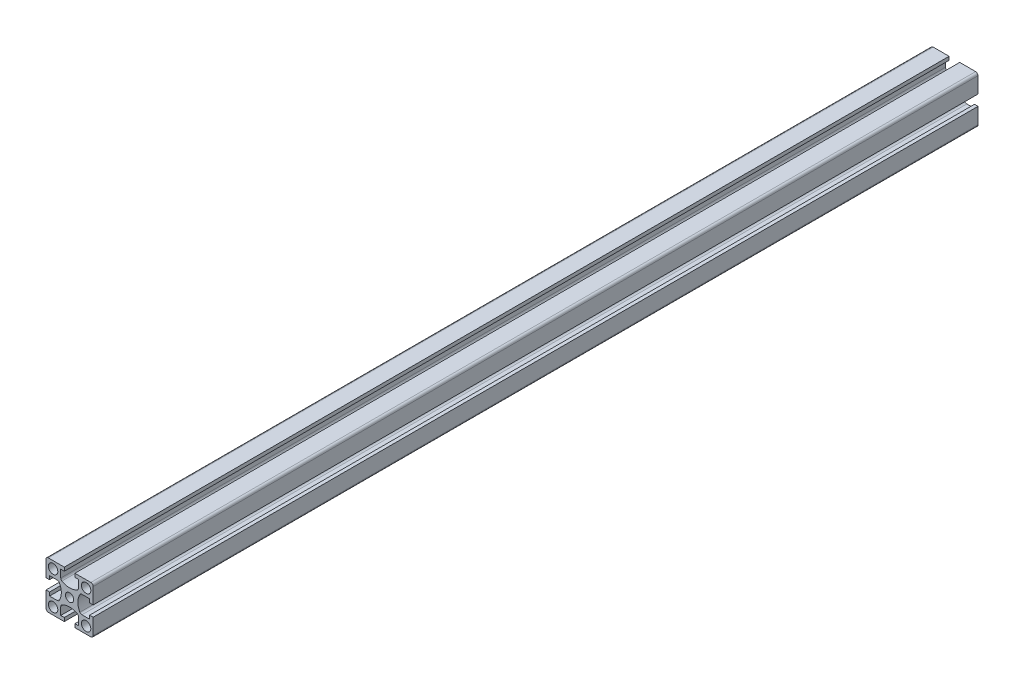
SolidWorks part; units mm, degrees
ref_plane "Front Plane" through (0, 0, 0) normal (0, 0, 1) x (1, 0, 0)
ref_plane "Top Plane" through (0, 0, 0) normal (0, 1, 0) x (1, 0, 0)
ref_plane "Right Plane" through (0, 0, 0) normal (1, 0, 0) x (0, 0, -1)
sketch "Sketch1" plane through (0, 0, 0) normal (0, 0, 1) x (1, 0, 0)
  line L64 (-10, 9) -> (-10, 2.25)
  line L65 (-10, 2.25) -> (-8.5, 2.25)
  line L66 (-8.5, 2.25) -> (-8.5, 3.75)
  line L67 (-8.5, 3.75) -> (-5.2369, 3.75)
  line L68 (-5.2369, -3.75) -> (-8.5, -3.75)
  line L69 (-8.5, -3.75) -> (-8.5, -2.25)
  line L70 (-8.5, -2.25) -> (-10, -2.25)
  line L71 (-10, -2.25) -> (-10, -9)
  line L72 (-9, -10) -> (-2.25, -10)
  line L73 (-2.25, -10) -> (-2.25, -8.5)
  line L74 (-2.25, -8.5) -> (-3.75, -8.5)
  line L75 (-3.75, -8.5) -> (-3.75, -5.2369)
  line L76 (3.75, -5.2369) -> (3.75, -8.5)
  line L77 (3.75, -8.5) -> (2.25, -8.5)
  line L78 (2.25, -8.5) -> (2.25, -10)
  line L79 (2.25, -10) -> (9, -10)
  line L80 (10, -9) -> (10, -2.25)
  line L81 (10, -2.25) -> (8.5, -2.25)
  line L82 (8.5, -2.25) -> (8.5, -3.75)
  line L83 (8.5, -3.75) -> (5.2369, -3.75)
  line L84 (5.2369, 3.75) -> (8.5, 3.75)
  line L85 (8.5, 3.75) -> (8.5, 2.25)
  line L86 (8.5, 2.25) -> (10, 2.25)
  line L87 (10, 2.25) -> (10, 9)
  line L88 (9, 10) -> (2.25, 10)
  line L89 (2.25, 10) -> (2.25, 8.5)
  line L90 (2.25, 8.5) -> (3.75, 8.5)
  line L91 (3.75, 8.5) -> (3.75, 5.2369)
  line L92 (-3.75, 5.2369) -> (-3.75, 8.5)
  line L93 (-3.75, 8.5) -> (-2.25, 8.5)
  line L94 (-2.25, 8.5) -> (-2.25, 10)
  line L95 (-2.25, 10) -> (-9, 10)
  circle A5 centre (-7, -7) radius 2
  circle A6 centre (7, -7) radius 2
  circle A7 centre (7, 7) radius 2
  circle A8 centre (0, 0) radius 1.75
  circle A9 centre (-7, 7) radius 2
  arc A32 (-9, 10) -> (-10, 9) centre (-9, 9) ccw
  arc A33 (-4.3708, 3.25) -> (-5.2369, 3.75) centre (-5.2369, 2.75) ccw
  arc A34 (-4.3708, -3.25) -> (-4.3708, 3.25) centre (-10, 0) ccw
  arc A35 (-5.2369, -3.75) -> (-4.3708, -3.25) centre (-5.2369, -2.75) ccw
  arc A36 (-10, -9) -> (-9, -10) centre (-9, -9) ccw
  arc A37 (-3.25, -4.3708) -> (-3.75, -5.2369) centre (-2.75, -5.2369) ccw
  arc A38 (3.25, -4.3708) -> (-3.25, -4.3708) centre (0, -10) ccw
  arc A39 (3.75, -5.2369) -> (3.25, -4.3708) centre (2.75, -5.2369) ccw
  arc A40 (9, -10) -> (10, -9) centre (9, -9) ccw
  arc A41 (4.3708, -3.25) -> (5.2369, -3.75) centre (5.2369, -2.75) ccw
  arc A42 (4.3708, 3.25) -> (4.3708, -3.25) centre (10, 0) ccw
  arc A43 (5.2369, 3.75) -> (4.3708, 3.25) centre (5.2369, 2.75) ccw
  arc A44 (10, 9) -> (9, 10) centre (9, 9) ccw
  arc A45 (3.25, 4.3708) -> (3.75, 5.2369) centre (2.75, 5.2369) ccw
  arc A46 (-3.25, 4.3708) -> (3.25, 4.3708) centre (0, 10) ccw
  arc A47 (-3.75, 5.2369) -> (-3.25, 4.3708) centre (-2.75, 5.2369) ccw
extrude "Boss-Extrude1" add sketch "Sketch1" along normal blind 375
